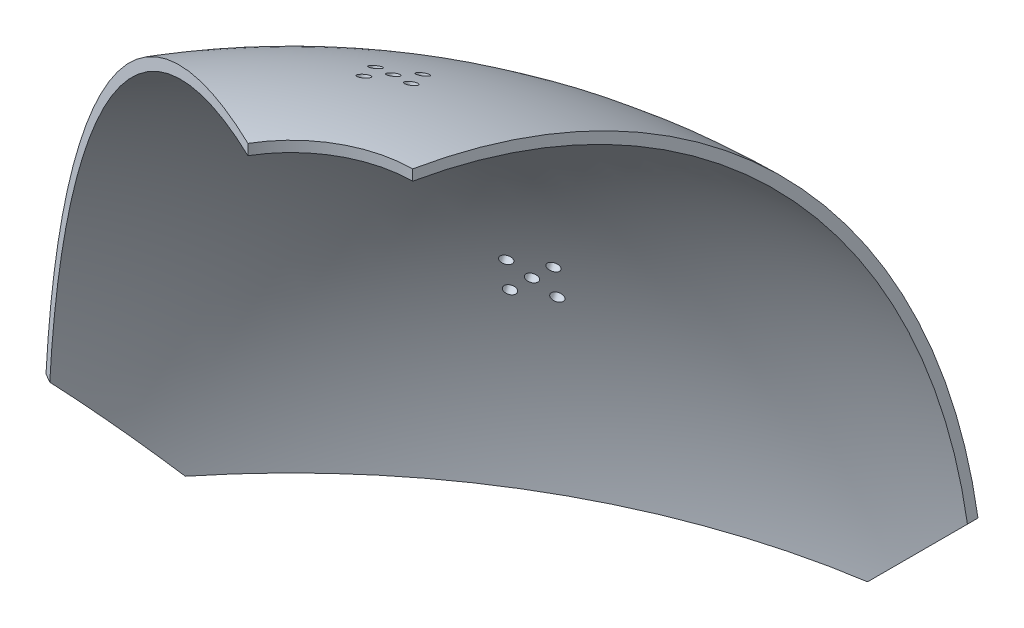
SolidWorks part; units mm, degrees
ref_plane "前视基准面" through (0, 0, 0) normal (0, 0, 1) x (1, 0, 0)
ref_plane "上视基准面" through (0, 0, 0) normal (0, 1, 0) x (1, 0, 0)
ref_plane "右视基准面" through (0, 0, 0) normal (1, 0, 0) x (0, 0, -1)
other "Configuration Table"
sketch "草图1" plane through (0, 0, 0) normal (0, 1, 0) x (1, 0, 0)
  line L0 (-92.5, 160.2147) -> (0, 0)
  line L1 (185, 0) -> (92.5, 160.2147)
  line L2 (92.5, 160.2147) -> (-92.5, 160.2147)
  line L3 (-92.5, 160.2147) -> (-185, 0)
  line L4 (-185, 0) -> (-92.5, -160.2147)
  line L5 (-92.5, -160.2147) -> (92.5, -160.2147)
  line L6 (92.5, -160.2147) -> (185, 0)
  line L7 (0, 0) -> (-185, 0)
  line L8 (0, 0) -> (185, 0)
  line L9 (0, 0) -> (-92.5, -160.2147)
  line L10 (0, 0) -> (92.5, -160.2147)
  line L11 (0, 0) -> (92.9816, 159.3805)
  line L12 (-138.75, -80.1073) -> (138.75, 80.1073)
  circle A0 centre (0, 0) radius 20
  circle A1 centre (0, 0) radius 160.2147 construction
  dimension "D1" = 185
sketch "草图2" plane through (0, 0, 0) normal (1, 0, 0) x (0, 0, -1)
  line L0 (0, 197) -> (0, 200)
  line L1 (197, 0) -> (200, 0)
  line L2 (0, 0) -> (139.3, 139.3)
  line L3 (160.2147, 0) -> (0, 0) construction
  line L4 (139.3, 139.3) -> (197, 0)
  circle A0 centre (0, 0) radius 200
  circle A1 centre (0, 0) radius 197
  dimension "D1" = 400
  dimension "D2" = 394
  dimension "D3" = 45
revolve "旋转1" add sketch "草图2" angle 60 about L0
ref_plane "基准面1" through (0, 0, 0) normal (-0.866, 0, 0.5) x (0.5, 0, 0.866)
ref_plane "基准面3" through (0, 0, 0) normal (0.5, 0, 0.866) x (0.866, 0, -0.5)
ref_plane "基准面2" through (0, 0, 0) normal (-0.1994, 0.9171, -0.3453) x (0.866, 0, -0.5)
sketch "草图8" plane through (0, 0, 0) normal (-0.1994, 0.9171, -0.3453) x (0.866, 0, -0.5)
  line L0 (-4.9497, 4.9497) -> (0, 0) construction
  line L1 (-160.2147, 0) -> (160.2147, 0) construction
  circle A0 centre (0, 0) radius 7 construction
  circle A1 centre (0, 0) radius 1.6
  circle A2 centre (-4.9497, 4.9497) radius 1.6
  circle A3 centre (4.9497, 4.9497) radius 1.6
  circle A4 centre (4.9497, -4.9497) radius 1.6
  circle A5 centre (-4.9497, -4.9497) radius 1.6
  point P17 (0, 0)
  dimension "D1" = 14
  dimension "D3" = 3.2
  dimension "D2" = 45
  dimension "D4" = 4
extrude "切除-拉伸3" cut sketch "草图8" along normal through all
ref_plane "基准面4" through (0, 0, 0) normal (-0.4769, 0.3007, -0.8259) x (0.866, 0, -0.5)
sketch "草图10" plane through (0, 0, 0) normal (-0.4769, 0.3007, -0.8259) x (0.866, 0, -0.5)
  line L0 (-4.9497, 4.9497) -> (0, 0) construction
  line L1 (0, 55.6306) -> (0, 0) construction
  circle A0 centre (0, 0) radius 7 construction
  circle A1 centre (0, 0) radius 1.6
  circle A3 centre (-4.9497, 4.9497) radius 1.6
  circle A4 centre (4.9497, 4.9497) radius 1.6
  circle A5 centre (4.9497, -4.9497) radius 1.6
  circle A6 centre (-4.9497, -4.9497) radius 1.6
  point P17 (0, 0)
  dimension "D1" = 14
  dimension "D3" = 3.2
  dimension "D2" = 45
  dimension "D4" = 4
extrude "切除-拉伸4" cut sketch "草图10" along normal through all
sketch "草图11" plane through (0, 0, 0) normal (-0.866, 0, 0.5) x (0.5, 0, 0.866)
  line L0 (0, 200) -> (0, 0) construction
  line L1 (160.2147, 0) -> (-160.2147, 0) construction
  line L3 (0, 200) -> (-35, 200)
  line L4 (0, 200) -> (0, 180)
  line L5 (0, 180) -> (-35, 180)
  line L6 (-35, 200) -> (-35, 180)
  dimension "D1" = 35
  dimension "D2" = 20
revolve "切除-旋转1" cut sketch "草图11" angle 360 about L0
chamfer "倒角1" distance 30 angle 45 2 edges at (-171.906, 0, -99.25) (0, 0, -198.5)
sketch "草图12" plane through (0, 0, 0) normal (0, -1, 0) x (1, 0, 0)
  line L0 (0, 0) -> (-170.7056, -100.5533)
  line L1 (-138.75, 80.1073) -> (138.75, -80.1073) construction
  line L2 (-170.7056, -100.5533) -> (-192.4181, -57.0494)
  line L3 (-192.4181, -57.0494) -> (0, 0)
  line L4 (0, 0) -> (-1.7426, -199.6812)
  line L5 (-1.7426, -199.6812) -> (64.8095, -200.262)
  line L6 (64.8095, -200.262) -> (0, 0)
  line L7 (0, -194.7023) -> (0, -35) construction
  line L8 (-30.3109, -17.5) -> (-168.6172, -97.3512) construction
  dimension "D1" = 0.5
  dimension "D2" = 0.5
extrude "切除-拉伸5" cut sketch "草图12" against normal through all contours L3 L2 L0 | L5 L6 L4
